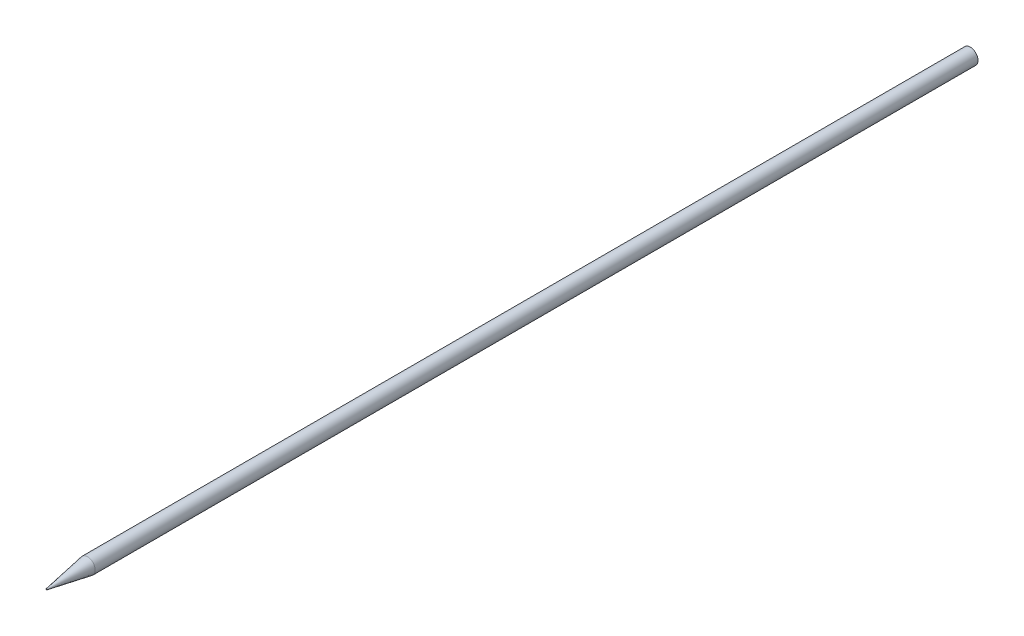
SolidWorks part; units mm, degrees
ref_plane "Front Plane" through (0, 0, 0) normal (0, 0, 1) x (1, 0, 0)
ref_plane "Top Plane" through (0, 0, 0) normal (0, 1, 0) x (1, 0, 0)
ref_plane "Right Plane" through (0, 0, 0) normal (1, 0, 0) x (0, 0, -1)
sketch "Sketch1" plane through (0, 0, 0) normal (0, 0, 1) x (1, 0, 0)
  circle A0 centre (0, 0) radius 0.1905
  dimension "D1" = 0.381
extrude "Boss-Extrude1" add sketch "Sketch1" along normal blind 22.86
chamfer "Chamfer1" distance 1.016 angle 10 1 edges at (0.1905, 0, 22.86)
